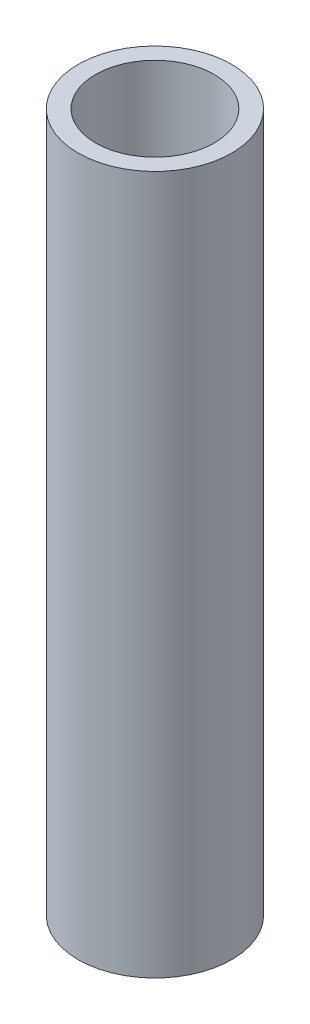
SolidWorks part; units mm, degrees
material "PVC 0.007 Plasticized"
ref_plane "Front Plane" through (0, 0, 0) normal (0, 0, 1) x (1, 0, 0)
ref_plane "Top Plane" through (0, 0, 0) normal (0, 1, 0) x (1, 0, 0)
ref_plane "Right Plane" through (0, 0, 0) normal (1, 0, 0) x (0, 0, -1)
sketch "Sketch1" plane through (0, 0, 0) normal (0, 1, 0) x (1, 0, 0)
  circle A0 centre (0, 0) radius 11
  circle A1 centre (0, 0) radius 8.5
extrude "Boss-Extrude1" add sketch "Sketch1" along normal blind 100
